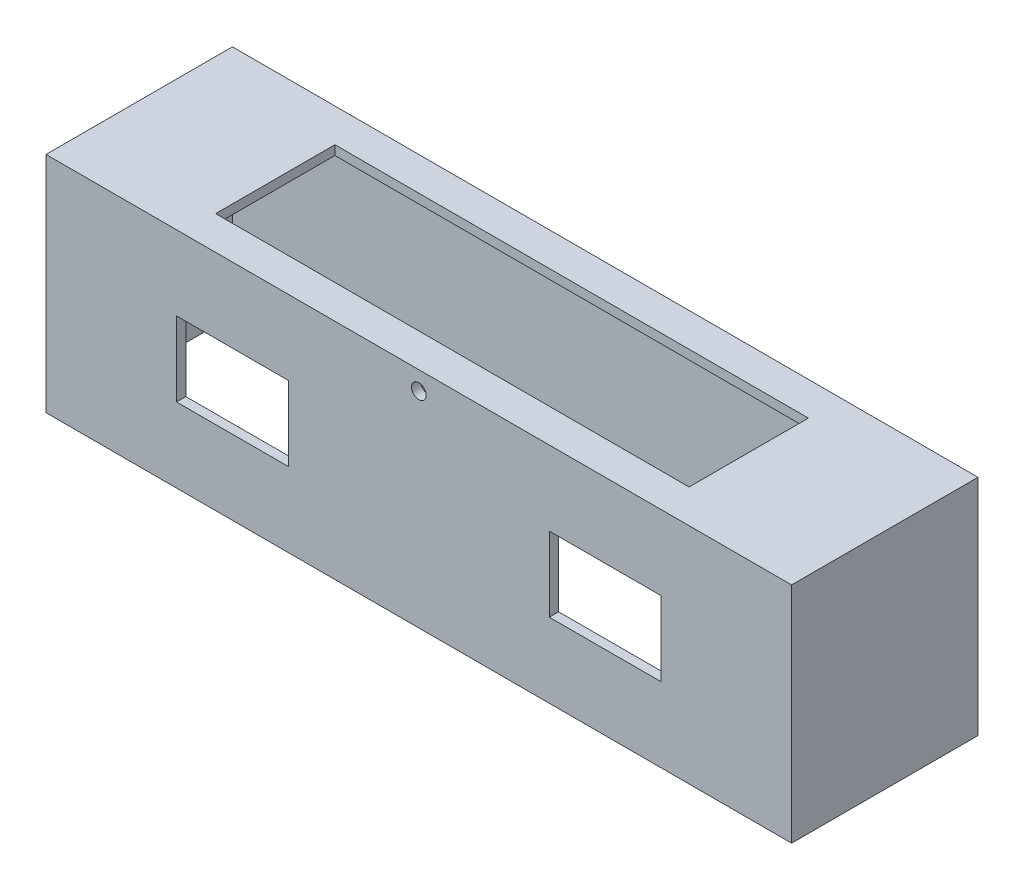
SolidWorks part; units mm, degrees
ref_plane "Front" through (0, 0, 0) normal (0, 0, 1) x (1, 0, 0)
ref_plane "Top" through (0, 0, 0) normal (0, 1, 0) x (1, 0, 0)
ref_plane "Right" through (0, 0, 0) normal (1, 0, 0) x (0, 0, -1)
sketch "Sketch1" plane through (0, 0, 0) normal (0, 1, 0) x (1, 0, 0)
  line L1 (-127, 31.75) -> (127, 31.75)
  line L2 (-127, 31.75) -> (-127, -31.75)
  line L3 (-127, -31.75) -> (127, -31.75)
  line L4 (127, 31.75) -> (127, -31.75)
  line L5 (-127, 31.75) -> (127, -31.75) construction
  line L6 (-127, -31.75) -> (127, 31.75) construction
  point P0 (0, 0)
  dimension "D1" = 63.5
  dimension "D2" = 254
extrude "Boss-Extrude1" add sketch "Sketch1" along normal blind 76.2 contours L2 L3 L4 L1
shell "Shell1" thickness 3.175
sketch "Sketch2" plane through (0, 0, 31.75) normal (0, 0, 1) x (1, 0, 0)
  line L0 (-127, 76.2) -> (-127, 0) construction
  line L1 (-82.55, 50.8) -> (-44.45, 50.8)
  line L2 (-82.55, 50.8) -> (-82.55, 25.4)
  line L3 (-82.55, 25.4) -> (-44.45, 25.4)
  line L4 (-44.45, 50.8) -> (-44.45, 25.4)
  line L5 (-82.55, 50.8) -> (-44.45, 25.4) construction
  line L6 (-82.55, 25.4) -> (-44.45, 50.8) construction
  line L11 (82.55, 25.4) -> (44.45, 25.4)
  line L12 (44.45, 50.8) -> (44.45, 25.4)
  line L13 (0, -41.91) -> (0, 41.91) construction
  line L14 (82.55, 50.8) -> (44.45, 50.8)
  line L15 (82.55, 50.8) -> (82.55, 25.4)
  point P0 (-63.5, 38.1)
  point P12 (-127, 38.1)
  dimension "D1" = 63.5
  dimension "D2" = 25.4
  dimension "D3" = 38.1
extrude "Cut-Extrude1" cut sketch "Sketch2" against normal up to next contours L15 L14 L12 L11 | L2 L3 L4 L1
sketch "Sketch3" plane through (0, 0, -31.75) normal (0, 0, -1) x (-1, 0, 0)
  line L0 (0, 41.91) -> (0, -41.91) construction
  line L1 (127, 76.2) -> (-127, 76.2) construction
  circle A0 centre (0, 69.85) radius 2.5
  dimension "D1" = 5
  dimension "D2" = 6.35
extrude "Cut-Extrude2" cut sketch "Sketch3" against normal through all
sketch "Sketch4" plane through (0, 76.2, 0) normal (0, 1, 0) x (1, 0, 0)
  line L1 (-80.645, 20.32) -> (80.645, 20.32)
  line L2 (-80.645, 20.32) -> (-80.645, -20.32)
  line L3 (-80.645, -20.32) -> (80.645, -20.32)
  line L4 (80.645, 20.32) -> (80.645, -20.32)
  line L5 (-80.645, 20.32) -> (80.645, -20.32) construction
  line L6 (-80.645, -20.32) -> (80.645, 20.32) construction
  point P0 (0, 0)
  dimension "D1" = 40.64
  dimension "D2" = 161.29
extrude "Cut-Extrude3" cut sketch "Sketch4" against normal through all
sketch "Sketch5" plane through (0, 0, 0) normal (1, 0, 0) x (0, 0, -1)
  line L0 (28.575, 0) -> (-28.575, 0) construction
  line L1 (-28.575, 0) -> (-28.575, 73.025) construction
  line L2 (-28.575, 73.025) -> (28.575, 73.025) construction
  line L3 (28.575, 73.025) -> (28.575, 0) construction
  line L4 (-31.75, 0) -> (31.75, 0) construction
  line L5 (31.75, 0) -> (31.75, 76.2) construction
  line L6 (31.75, 76.2) -> (-31.75, 76.2) construction
  line L7 (-31.75, 76.2) -> (-31.75, 0) construction
  line L8 (28.575, 0) -> (-28.575, 0)
  line L9 (-28.575, 0) -> (-28.575, 73.025)
  line L10 (-28.575, 73.025) -> (28.575, 73.025)
  line L11 (28.575, 73.025) -> (28.575, 0)
  line L12 (-31.75, 0) -> (31.75, 0)
  line L13 (31.75, 0) -> (31.75, 76.2)
  line L14 (31.75, 76.2) -> (-31.75, 76.2)
  line L15 (-31.75, 76.2) -> (-31.75, 0)
  line L16 (-31.75, 76.2) -> (-66.6017, 0)
  line L17 (-66.6017, 0) -> (-60.7706, 0)
  line L18 (-60.5224, 3.175) -> (-28.575, 73.025)
  line L19 (-60.7706, 0) -> (-28.575, 0)
  line L20 (-60.5224, 3.175) -> (-28.575, 3.175)
  point P8 (-59.8463, 4.6531)
  dimension "D1" = 3.175
  dimension "D2" = 3.175
